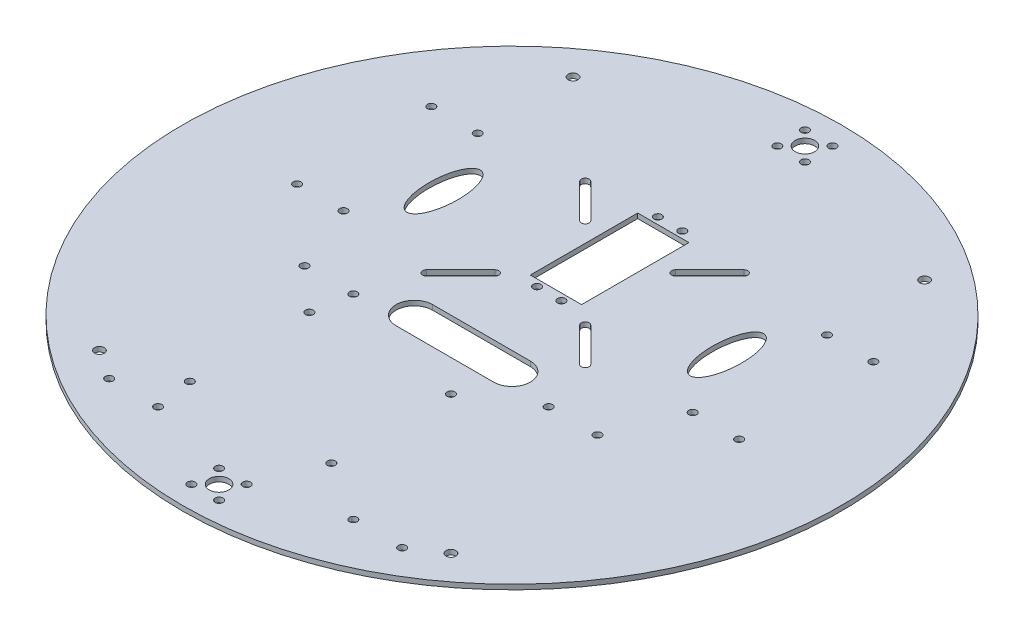
SolidWorks part; units mm, degrees
ref_plane "前视基准面" through (0, 0, 0) normal (0, 0, 1) x (1, 0, 0)
ref_plane "上视基准面" through (0, 0, 0) normal (0, 1, 0) x (1, 0, 0)
ref_plane "右视基准面" through (0, 0, 0) normal (1, 0, 0) x (0, 0, -1)
sketch "草图1" plane through (0, 0, 0) normal (0, 1, 0) x (1, 0, 0)
  line L0 (0, 135) -> (0, -135) construction
  line L1 (-80, 80) -> (80, 80) construction
  line L2 (-80, 80) -> (-80, -80) construction
  line L3 (-80, -80) -> (80, -80) construction
  line L4 (80, 80) -> (80, -80) construction
  line L5 (-80, 80) -> (80, -80) construction
  line L6 (-80, -80) -> (80, 80) construction
  line L7 (-135, 0) -> (135, 0) construction
  line L9 (-30, 60) -> (30, 60) construction
  line L10 (-30, 60) -> (-30, 0) construction
  line L11 (-30, 0) -> (30, 0) construction
  line L12 (30, 60) -> (30, 0) construction
  line L13 (-30, 60) -> (30, 0) construction
  line L14 (-30, 0) -> (30, 60) construction
  circle A0 centre (0, 0) radius 135
  point P17 (0, 0)
  point P19 (0, 30)
  dimension "D1" = 270
  dimension "D2" = 160
  dimension "D3" = 160
  dimension "D5" = 30
  dimension "D6" = 60
  dimension "D7" = 60
extrude "凸台-拉伸1" add sketch "草图1" along normal blind 2
sketch "云台安装孔" plane through (0, 2, 0) normal (0, 1, 0) x (1, 0, 0)
  line L0 (0, 135) -> (0, -135) construction
  line L1 (-135, 0) -> (135, 0) construction
  line L3 (-18.5, 48.5) -> (18.5, 48.5) construction
  line L4 (-18.5, 48.5) -> (-18.5, 11.5) construction
  line L5 (-18.5, 11.5) -> (18.5, 11.5) construction
  line L6 (18.5, 48.5) -> (18.5, 11.5) construction
  line L7 (-18.5, 48.5) -> (18.5, 11.5) construction
  line L8 (-18.5, 11.5) -> (18.5, 48.5) construction
  line L9 (-62.9961, -18.6558) -> (62.9961, -18.6558) construction
  line L10 (-62.9961, -18.6558) -> (-62.9961, -86.2012) construction
  line L11 (-62.9961, -86.2012) -> (62.9961, -86.2012) construction
  line L12 (62.9961, -18.6558) -> (62.9961, -86.2012) construction
  line L13 (-62.9961, -18.6558) -> (62.9961, -86.2012) construction
  line L14 (-62.9961, -86.2012) -> (62.9961, -18.6558) construction
  line L15 (-10.5, 62) -> (10.5, 62)
  line L16 (-10.5, 62) -> (-10.5, 18)
  line L17 (-10.5, 18) -> (10.5, 18)
  line L18 (10.5, 62) -> (10.5, 18)
  line L19 (-10.5, 62) -> (10.5, 18) construction
  line L20 (-10.5, 18) -> (10.5, 62) construction
  line L21 (-5, 64.75) -> (5, 64.75) construction
  line L22 (-5, 64.75) -> (-5, 15.25) construction
  line L23 (-5, 15.25) -> (5, 15.25) construction
  line L24 (5, 64.75) -> (5, 15.25) construction
  line L25 (-5, 64.75) -> (5, 15.25) construction
  line L26 (-5, 15.25) -> (5, 64.75) construction
  line L27 (-38.5, 68.5) -> (38.5, 68.5) construction
  line L28 (-38.5, 68.5) -> (-38.5, -8.5) construction
  line L29 (-38.5, -8.5) -> (38.5, -8.5) construction
  line L30 (38.5, 68.5) -> (38.5, -8.5) construction
  line L31 (-38.5, 68.5) -> (38.5, -8.5) construction
  line L32 (-38.5, -8.5) -> (38.5, 68.5) construction
  circle A0 centre (0, 0) radius 135 construction
  circle A1 centre (-5, 64.75) radius 1.6
  circle A2 centre (5, 64.75) radius 1.6
  circle A3 centre (-5, 15.25) radius 1.6
  circle A4 centre (5, 15.25) radius 1.6
  circle A5 centre (18.5, 48.5) radius 1.6
  circle A6 centre (18.5, 11.5) radius 1.6
  circle A7 centre (-18.5, 11.5) radius 1.6
  circle A8 centre (-18.5, 48.5) radius 1.6
  point P3 (0, 30)
  point P8 (0, 30)
  point P13 (0, -52.4285)
  point P18 (0, 40)
  point P23 (0, 40)
  point P50 (0, 30)
  dimension "D3" = 21
  dimension "D8" = 3.2
  dimension "D9" = 3.2
  dimension "D10" = 3.2
  dimension "D11" = 3.2
  dimension "D12" = 3.2
  dimension "D13" = 3.2
  dimension "D1" = 37
  dimension "D2" = 37
  dimension "D4" = 44
  dimension "D5" = 10
  dimension "D6" = 10
  dimension "D7" = 49.5
  dimension "D14" = 30
  dimension "D15" = 77
  dimension "D16" = 77
extrude "切除-拉伸1" cut sketch "云台安装孔" against normal blind 10
sketch "扩展板安装孔" plane through (0, 2, 0) normal (0, 1, 0) x (1, 0, 0)
  line L0 (0, 135) -> (0, -135) construction
  line L1 (15.5, -40.5) -> (15.5, -89.5) construction
  line L2 (-60, -25) -> (60, -25) construction
  line L3 (-60, -25) -> (-60, -105) construction
  line L4 (-60, -105) -> (60, -105) construction
  line L5 (60, -25) -> (60, -105) construction
  line L6 (-60, -25) -> (60, -105) construction
  line L7 (-60, -105) -> (60, -25) construction
  line L8 (-40, -25) -> (40, -25) construction
  line L9 (-40, -25) -> (-40, -105) construction
  line L10 (-40, -105) -> (40, -105) construction
  line L11 (40, -25) -> (40, -105) construction
  line L12 (-40, -25) -> (40, -105) construction
  line L13 (-40, -105) -> (40, -25) construction
  line L14 (-42.5, -40.5) -> (42.5, -40.5) construction
  line L15 (-42.5, -40.5) -> (-42.5, -89.5) construction
  line L16 (-42.5, -89.5) -> (42.5, -89.5) construction
  line L17 (42.5, -40.5) -> (42.5, -89.5) construction
  line L18 (-42.5, -40.5) -> (42.5, -89.5) construction
  line L19 (-42.5, -89.5) -> (42.5, -40.5) construction
  circle A0 centre (0, 0) radius 135 construction
  circle A1 centre (-60, -25) radius 1.6
  circle A2 centre (-40, -25) radius 1.6
  circle A3 centre (40, -25) radius 1.6
  circle A4 centre (60, -25) radius 1.6
  circle A5 centre (60, -105) radius 1.6
  circle A6 centre (40, -105) radius 1.6
  circle A7 centre (-40, -105) radius 1.6
  circle A8 centre (-60, -105) radius 1.6
  circle A9 centre (-42.5, -89.5) radius 1.6
  circle A12 centre (-42.5, -40.5) radius 1.6
  circle A13 centre (15.5, -40.5) radius 1.6
  circle A14 centre (15.5, -89.5) radius 1.6
  point P5 (0, -65)
  point P10 (0, -65)
  point P15 (0, -65)
  dimension "D7" = 65
  dimension "D1" = 120
  dimension "D2" = 80
  dimension "D3" = 80
  dimension "D4" = 85
  dimension "D5" = 49
  dimension "D6" = 58
extrude "切除-拉伸2" cut sketch "扩展板安装孔" against normal blind 10
sketch "草图4" plane through (0, 2, 0) normal (0, 1, 0) x (1, 0, 0)
  line L0 (0, 135) -> (0, -135) construction
  line L1 (-135, 0) -> (135, 0) construction
  line L2 (-20, -12.5) -> (20, -12.5)
  line L3 (-20, -12.5) -> (-20, -27.5) construction
  line L4 (-20, -27.5) -> (20, -27.5)
  line L5 (20, -12.5) -> (20, -27.5) construction
  line L6 (-20, -12.5) -> (20, -27.5) construction
  line L7 (-20, -27.5) -> (20, -12.5) construction
  line L8 (-72, 97) -> (72, 97) construction
  line L9 (-72, 97) -> (-72, -97) construction
  line L10 (-72, -97) -> (72, -97) construction
  line L11 (72, 97) -> (72, -97) construction
  line L12 (-72, 97) -> (72, -97) construction
  line L13 (-72, -97) -> (72, 97) construction
  circle A0 centre (0, 0) radius 135 construction
  arc A1 (-20, -12.5) -> (-20, -27.5) centre (-20, -20) ccw
  arc A2 (20, -12.5) -> (20, -27.5) centre (20, -20) cw
  circle A3 centre (-72, 97) radius 2
  circle A4 centre (72, 97) radius 2
  circle A5 centre (72, -97) radius 2
  circle A6 centre (-72, -97) radius 2
  circle A7 centre (0, -120) radius 4
  circle A8 centre (0, 120) radius 8 construction
  circle A9 centre (-5.6569, -125.6569) radius 1.6
  circle A10 centre (-5.6569, -114.3431) radius 1.6
  circle A11 centre (5.6569, -114.3431) radius 1.6
  circle A12 centre (5.6569, -125.6569) radius 1.6
  circle A13 centre (5.6569, 125.6569) radius 1.6
  circle A14 centre (5.6569, 114.3431) radius 1.6
  circle A15 centre (-5.6569, 114.3431) radius 1.6
  circle A16 centre (-5.6569, 125.6569) radius 1.6
  circle A17 centre (0, -120) radius 8 construction
  circle A18 centre (0, 120) radius 4
  point P5 (0, -20)
  point P12 (0, 0)
  point P41 (0, -120)
  point P50 (0, 120)
  dimension "D5" = 120
  dimension "D6" = 4
  dimension "D7" = 4
  dimension "D8" = 4
  dimension "D9" = 4
  dimension "D12" = 4
  dimension "D10" = 16
  dimension "D11" = 4
  dimension "D1" = 15
  dimension "D2" = 40
  dimension "D3" = 144
  dimension "D4" = 194
  dimension "D13" = 20
extrude "切除-拉伸3" cut sketch "草图4" against normal blind 10
sketch "草图5" plane through (0, 2, 0) normal (0, 1, 0) x (1, 0, 0)
  line L0 (-31.3686, 63.6314) -> (-17.3686, 49.6314)
  line L1 (-10.5, 62) -> (-10.5, 18) construction
  line L2 (-33.6314, 61.3686) -> (-19.6314, 47.3686)
  line L3 (-32.5, 62.5) -> (32.5, 62.5) construction
  line L4 (-32.5, 62.5) -> (-32.5, -2.5) construction
  line L5 (-32.5, -2.5) -> (32.5, -2.5) construction
  line L6 (32.5, 62.5) -> (32.5, -2.5) construction
  line L7 (-32.5, 62.5) -> (32.5, -2.5) construction
  line L8 (-32.5, -2.5) -> (32.5, 62.5) construction
  line L9 (33.6314, 61.3686) -> (19.6314, 47.3686)
  line L10 (31.3686, 63.6314) -> (17.3686, 49.6314)
  line L11 (31.3686, -3.6314) -> (17.3686, 10.3686)
  line L12 (33.6314, -1.3686) -> (19.6314, 12.6314)
  line L13 (-33.6314, -1.3686) -> (-19.6314, 12.6314)
  line L14 (-31.3686, -3.6314) -> (-17.3686, 10.3686)
  arc A0 (33.6314, 61.3686) -> (31.3686, 63.6314) centre (32.5, 62.5) ccw
  arc A1 (-19.6314, 47.3686) -> (-17.3686, 49.6314) centre (-18.5, 48.5) ccw
  arc A2 (-31.3686, 63.6314) -> (-33.6314, 61.3686) centre (-32.5, 62.5) ccw
  arc A3 (17.3686, 49.6314) -> (19.6314, 47.3686) centre (18.5, 48.5) ccw
  arc A4 (31.3686, -3.6314) -> (33.6314, -1.3686) centre (32.5, -2.5) ccw
  arc A5 (19.6314, 12.6314) -> (17.3686, 10.3686) centre (18.5, 11.5) ccw
  arc A6 (-33.6314, -1.3686) -> (-31.3686, -3.6314) centre (-32.5, -2.5) ccw
  arc A7 (-17.3686, 10.3686) -> (-19.6314, 12.6314) centre (-18.5, 11.5) ccw
  point P5 (0, 30)
  point P35 (0, 30)
  dimension "D4" = 3.2
  dimension "D1" = 30
  dimension "D2" = 10.5
  dimension "D3" = 65
  dimension "D5" = 1.6
  dimension "D6" = 4
extrude "切除-拉伸4" cut sketch "草图5" against normal blind 10
sketch "草图6" plane through (0, 2, 0) normal (0, 1, 0) x (1, 0, 0)
  line L0 (33.6314, -3.6314) -> (33.6314, 63.6314) construction
  line L1 (33.6314, 30) -> (118.3005, 30) construction
  line L2 (0, 120) -> (0, -27.5) construction
  line L3 (-20, -27.5) -> (20, -27.5) construction
  line L4 (-33.6314, -3.6314) -> (-33.6314, 63.6314) construction
  line L5 (71.5372, 2.5) -> (90.5372, 2.5) construction
  line L6 (71.5372, 2.5) -> (71.5372, 57.5) construction
  line L7 (71.5372, 57.5) -> (90.5372, 57.5) construction
  line L8 (90.5372, 2.5) -> (90.5372, 57.5) construction
  line L9 (71.5372, 2.5) -> (90.5372, 57.5) construction
  line L10 (71.5372, 57.5) -> (90.5372, 2.5) construction
  line L11 (-33.6314, 30) -> (-118.3005, 30) construction
  line L12 (-71.5372, 57.5) -> (-90.5372, 57.5) construction
  line L13 (-71.5372, 2.5) -> (-90.5372, 2.5) construction
  line L14 (-71.5372, 2.5) -> (-71.5372, 57.5) construction
  line L15 (-90.5372, 2.5) -> (-90.5372, 57.5) construction
  line L16 (-71.5372, 57.5) -> (-90.5372, 2.5) construction
  line L17 (-71.5372, 2.5) -> (-90.5372, 57.5) construction
  arc A0 (31.3686, -3.6314) -> (33.6314, -1.3686) centre (32.5, -2.5) ccw construction
  arc A1 (33.6314, 61.3686) -> (31.3686, 63.6314) centre (32.5, 62.5) ccw construction
  circle A2 centre (71.5372, 2.5) radius 1.6
  circle A3 centre (90.5372, 2.5) radius 1.6
  circle A4 centre (90.5372, 57.5) radius 1.6
  circle A5 centre (71.5372, 57.5) radius 1.6
  circle A6 centre (-71.5372, 57.5) radius 1.6
  circle A7 centre (-90.5372, 2.5) radius 1.6
  circle A8 centre (-71.5372, 2.5) radius 1.6
  circle A9 centre (-90.5372, 57.5) radius 1.6
  ellipse E0 centre (-58.0311, 30) end of major axis (-58.0311, 15) minor radius 6
  ellipse E1 centre (58.0311, 30) end of major axis (58.0311, 45) minor radius 6
  point P15 (81.0372, 30)
  point P30 (-90.5372, 57.5)
  dimension "D3" = 6
  dimension "D1" = 19
  dimension "D2" = 55
  dimension "D4" = 15
extrude "切除-拉伸7" cut sketch "草图6" against normal blind 10 contours A8 | A7 | A9 | A6 | A2 | A3 | A4 | A5 | E0 | E1
